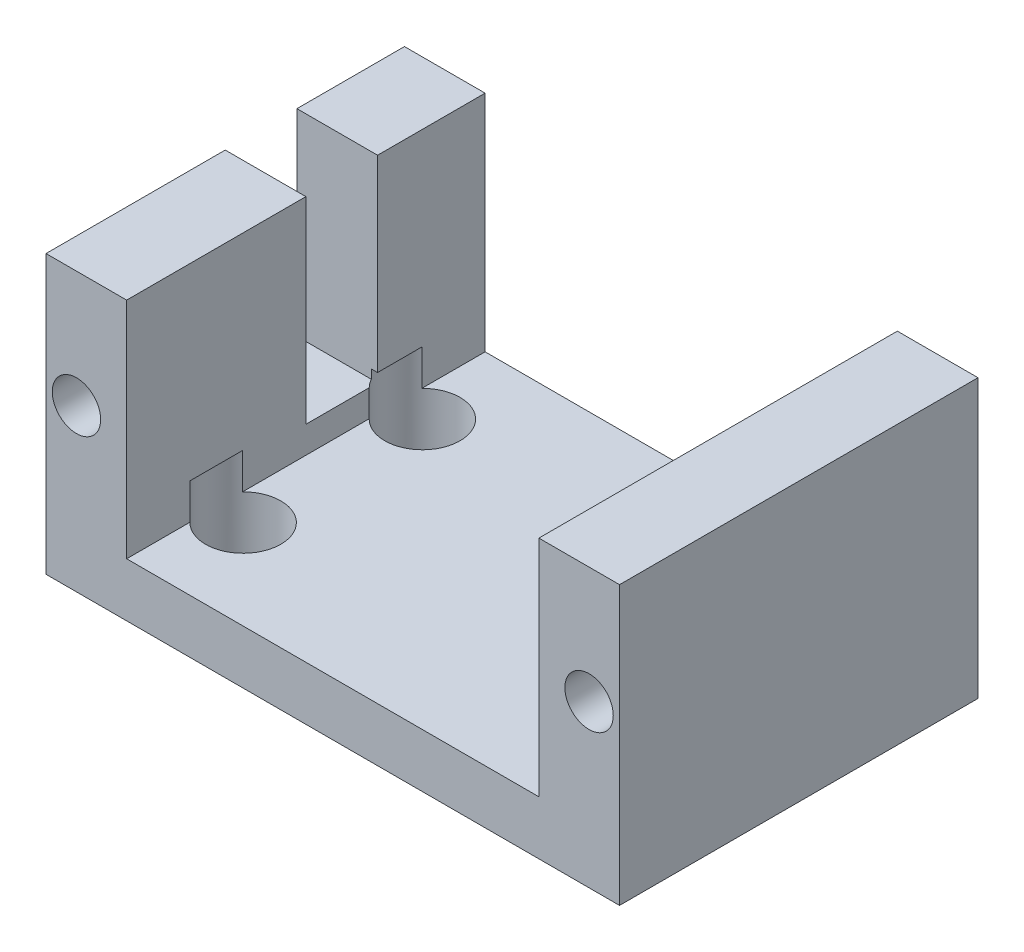
SolidWorks part; units mm, degrees
ref_plane "Спереди" through (0, 0, 0) normal (0, 0, 1) x (1, 0, 0)
ref_plane "Сверху" through (0, 0, 0) normal (0, 1, 0) x (1, 0, 0)
ref_plane "Справа" through (0, 0, 0) normal (1, 0, 0) x (0, 0, -1)
sketch "Эскиз4" plane through (0, 0, 0) normal (0, 0, 1) x (1, 0, 0)
  line L1 (-16, -7.75) -> (16, -7.75)
  line L2 (-16, -7.75) -> (-16, 7.75)
  line L3 (-16, 7.75) -> (16, 7.75)
  line L4 (16, -7.75) -> (16, 7.75)
  line L5 (-16, -7.75) -> (16, 7.75) construction
  line L6 (-16, 7.75) -> (16, -7.75) construction
  point P0 (0, 0)
  dimension "D1" = 32
  dimension "D2" = 15.5
extrude "Бобышка-Вытянуть2" add sketch "Эскиз4" along normal blind 20
sketch "Эскиз6" plane through (0, 0, 0) normal (0, 0, -1) x (-1, 0, 0)
  line L0 (-16, 7.75) -> (16, 7.75) construction
  line L1 (-11.5, 7.75) -> (11.5, 7.75)
  line L2 (-11.5, 7.75) -> (-11.5, -4.75)
  line L3 (-11.5, -4.75) -> (11.5, -4.75)
  line L4 (11.5, 7.75) -> (11.5, -4.75)
  line L5 (16, -7.75) -> (-16, -7.75) construction
  point P6 (0, -4.75)
  dimension "D1" = 23
  dimension "D2" = 3
extrude "Вырез-Вытянуть1" cut sketch "Эскиз6" against normal through all
sketch "Эскиз7" plane through (-16, 0, 0) normal (-1, 0, 0) x (0, 0, 1)
  line L0 (20, 7.75) -> (0, 7.75) construction
  line L1 (6, 7.75) -> (10, 7.75)
  line L2 (6, 7.75) -> (6, -3.25)
  line L3 (6, -3.25) -> (10, -3.25)
  line L4 (10, 7.75) -> (10, -3.25)
  line L5 (0, 7.75) -> (0, -7.75) construction
  dimension "D1" = 4
  dimension "D2" = 11
  dimension "D3" = 6
extrude "Вырез-Вытянуть2" cut sketch "Эскиз7" against normal up to next
sketch "Эскиз9" plane through (0, 0, 20) normal (0, 0, 1) x (1, 0, 0)
  line L3 (-14.3, 1.25) -> (14.3, 1.25) construction
  line L5 (15.8, 7.25) -> (15.8, -4.75) construction
  circle A4 centre (-14.3, 1.25) radius 1.35
  circle A6 centre (14.3, 1.25) radius 1.35
  point P5 (15.8, 1.25)
  point P7 (0, 1.25)
  dimension "D2" = 2.7
  dimension "D1" = 28.6
extrude "Вырез-Вытянуть3" cut sketch "Эскиз9" against normal blind 10
sketch "Эскиз11" plane through (0, -7.75, 0) normal (0, -1, 0) x (1, 0, 0)
  line L0 (16, 20) -> (16, 0) construction
  line L1 (-10, 5) -> (10, 5) construction
  line L2 (-10, 5) -> (-10, 15) construction
  line L3 (-10, 15) -> (10, 15) construction
  line L4 (10, 5) -> (10, 15) construction
  line L5 (-10, 5) -> (10, 15) construction
  line L6 (-10, 15) -> (10, 5) construction
  circle A0 centre (-10, 15) radius 2.1
  circle A1 centre (10, 15) radius 2.1
  circle A2 centre (10, 5) radius 2.1
  circle A3 centre (-10, 5) radius 2.1
  point P0 (0, 10)
  point P10 (16, 10)
  dimension "D1" = 4.2
  dimension "D2" = 20
  dimension "D3" = 10
extrude "Вырез-Вытянуть4" cut sketch "Эскиз11" against normal blind 5
